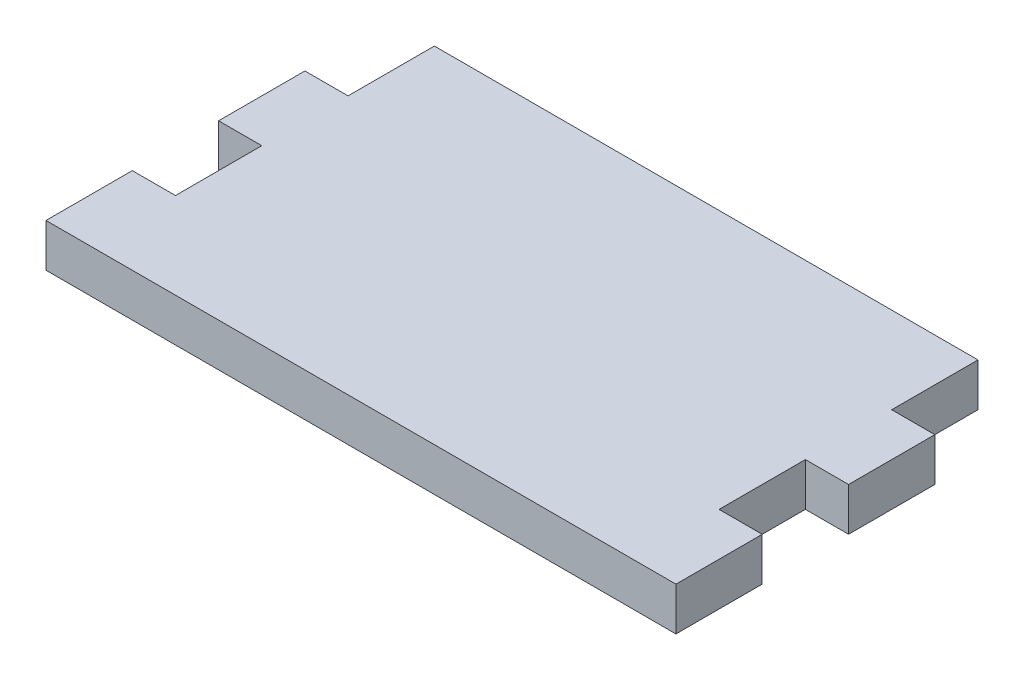
SolidWorks part; units mm, degrees
material "Acrylic (Medium-high impact)"
ref_plane "Front Plane" through (0, 0, 0) normal (0, 0, 1) x (1, 0, 0)
ref_plane "Top Plane" through (0, 0, 0) normal (0, 1, 0) x (1, 0, 0)
ref_plane "Right Plane" through (0, 0, 0) normal (1, 0, 0) x (0, 0, -1)
sketch "Sketch1" plane through (0, 0, 0) normal (0, 1, 0) x (1, 0, 0)
  line L0 (0, 0) -> (0, 6.35)
  line L1 (0, 6.35) -> (3.175, 6.35)
  line L2 (3.175, 6.35) -> (3.175, 12.7)
  line L3 (3.175, 12.7) -> (0, 12.7)
  line L4 (0, 12.7) -> (0, 19.05)
  line L5 (0, 19.05) -> (3.175, 19.05)
  line L6 (3.175, 19.05) -> (3.175, 25.4)
  line L7 (3.175, 25.4) -> (43.175, 25.4)
  line L8 (43.175, 25.4) -> (43.175, 19.05)
  line L9 (43.175, 19.05) -> (46.35, 19.05)
  line L10 (46.35, 19.05) -> (46.35, 12.7)
  line L11 (46.35, 12.7) -> (43.175, 12.7)
  line L12 (43.175, 12.7) -> (43.175, 6.35)
  line L13 (43.175, 6.35) -> (46.35, 6.35)
  line L14 (46.35, 6.35) -> (46.35, 0)
  line L15 (46.35, 0) -> (0, 0)
  dimension "D1" = 6.35
  dimension "D2" = 3.175
  dimension "D3" = 40
extrude "Boss-Extrude1" add sketch "Sketch1" along normal blind 3.175
